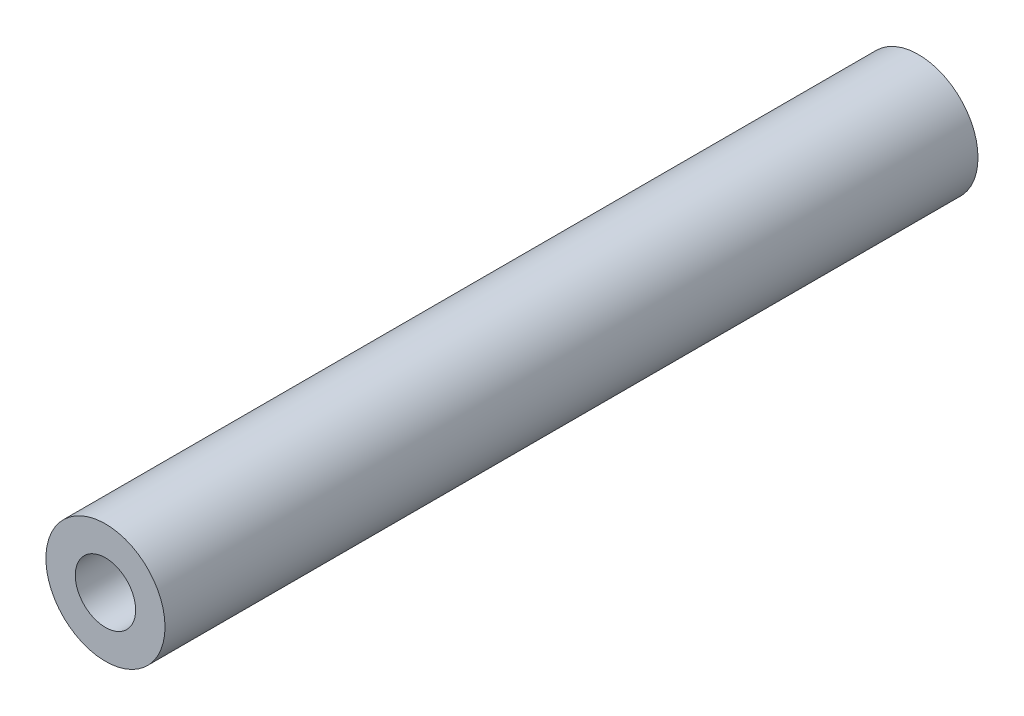
SolidWorks part; units mm, degrees
material "PTFE (general)"
ref_plane "Front Plane" through (0, 0, 0) normal (0, 0, 1) x (1, 0, 0)
ref_plane "Top Plane" through (0, 0, 0) normal (0, 1, 0) x (1, 0, 0)
ref_plane "Right Plane" through (0, 0, 0) normal (1, 0, 0) x (0, 0, -1)
sketch "Sketch1" plane through (0, 0, 0) normal (0, 0, 1) x (1, 0, 0)
  circle A0 centre (0, 0) radius 1.9558
  circle A1 centre (0, 0) radius 0.9906
  dimension "D1" = 3.9116
  dimension "D2" = 1.9812
extrude "Boss-Extrude1" add sketch "Sketch1" along normal mid plane 26.6954
